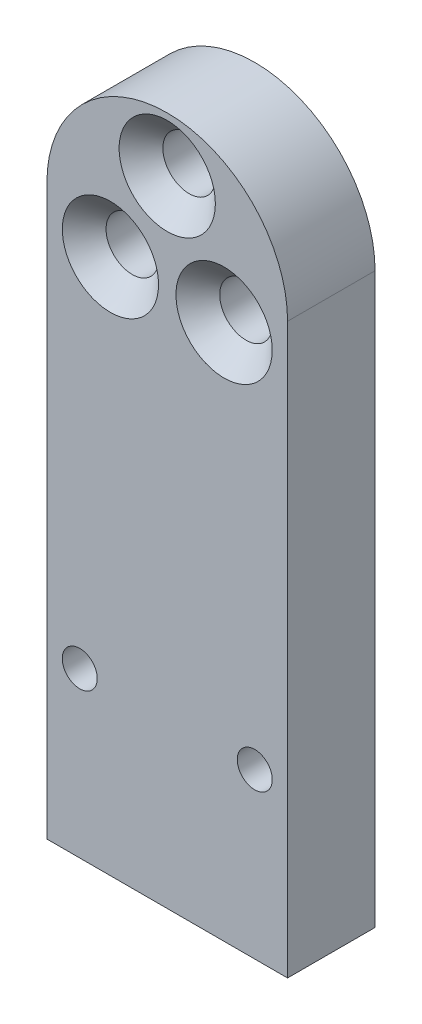
SolidWorks part; units mm, degrees
material "Liga 1060"
ref_plane "Plano frontal" through (0, 0, 0) normal (0, 0, 1) x (1, 0, 0)
ref_plane "Plano superior" through (0, 0, 0) normal (0, 1, 0) x (1, 0, 0)
ref_plane "Plano direito" through (0, 0, 0) normal (1, 0, 0) x (0, 0, -1)
sketch "Esboço1" plane through (0, 0, 0) normal (0, 0, 1) x (1, 0, 0)
  line L0 (-5.5, 0) -> (-5.5, -26)
  line L1 (5.5, 0) -> (5.5, -26)
  line L2 (5.5, -26) -> (-5.5, -26)
  arc A0 (5.5, 0) -> (-5.5, 0) centre (0, 0) ccw
  dimension "D1" = 11
  dimension "D2" = 26
extrude "Ressalto-extrusão1" add sketch "Esboço1" along normal blind 4
sketch "Esboço2" plane through (0, 0, 4) normal (0, 0, 1) x (1, 0, 0)
  circle A0 centre (0, 0) radius 3 construction
  point P3 (0, 3)
  point P11 (0, 0)
  dimension "D1" = 6
sketch "Esboço4" plane through (0, 0, 4) normal (0, 0, 1) x (1, 0, 0)
  line L0 (0, -26) -> (0, -18.5) construction
  line L1 (-5.5, -26) -> (5.5, -26) construction
  line L2 (-4, -18.5) -> (4, -18.5) construction
  dimension "D1" = 7.5
  dimension "D2" = 8
hole_wizard "Furo roscado de M21" positions "3DSketch3" profile "Esboço5" tap size "M2" standard "ISO" end condition through all
sketch3d "3DSketch3"
  point P0 (-4, -18.5, 4)
  point P6 (4, -18.5, 4)
sketch "Esboço5" plane through (-4, -18.5, 4) normal (1, 0, 0) x (0, -1, 0)
  line L0 (0, 0) -> (0, 4)
  line L1 (0, 4) -> (0.8, 4)
  line L2 (0.8, 4) -> (0.8, 0)
  line L5 (0.8, 0) -> (0, 0)
  line L11 (0, -6.35) -> (0, 107.95) construction
  dimension "Thru Tap Drill Dia." = 1.6
  dimension "Thru Tap Drill Depth" = 4
cosmetic thread "Rosca de furo1" parameters "D2"=2
cosmetic thread "Rosca de furo3" parameters "D2"=2
hole_wizard "Escareado para parafuso com cabeça escareada chata de M21" positions "3DSketch4" profile "Esboço6" countersink size "M2" standard "ISO" end condition through all
sketch3d "3DSketch4"
  point P0 (0, 3, 4)
sketch "Esboço6" plane through (0, 3, 4) normal (1, 0, 0) x (0, -1, 0)
  line L0 (0, 0) -> (0, 4)
  line L1 (0, 4) -> (1.2, 4)
  line L2 (1.2, 4) -> (1.2, 1)
  line L3 (1.2, 1) -> (2.2, 0)
  line L5 (2.2, 0) -> (0, 0)
  line L6 (-1.2, 1) -> (-2.2, 0) construction
  line L11 (0, -6.35) -> (0, 107.95) construction
  dimension "Thru Hole Dia." = 2.4
  dimension "Thru Hole Depth" = 4
  dimension "Near C'Sink Dia." = 4.4
  dimension "Near C'Sink Angle" = 90
pattern_circular "PadrãoCircular1" count 3 over 360 about axis through (0, 0, 0) along (0, 0, 1) of "Escareado para parafuso com cabeça escareada chata de M21"
